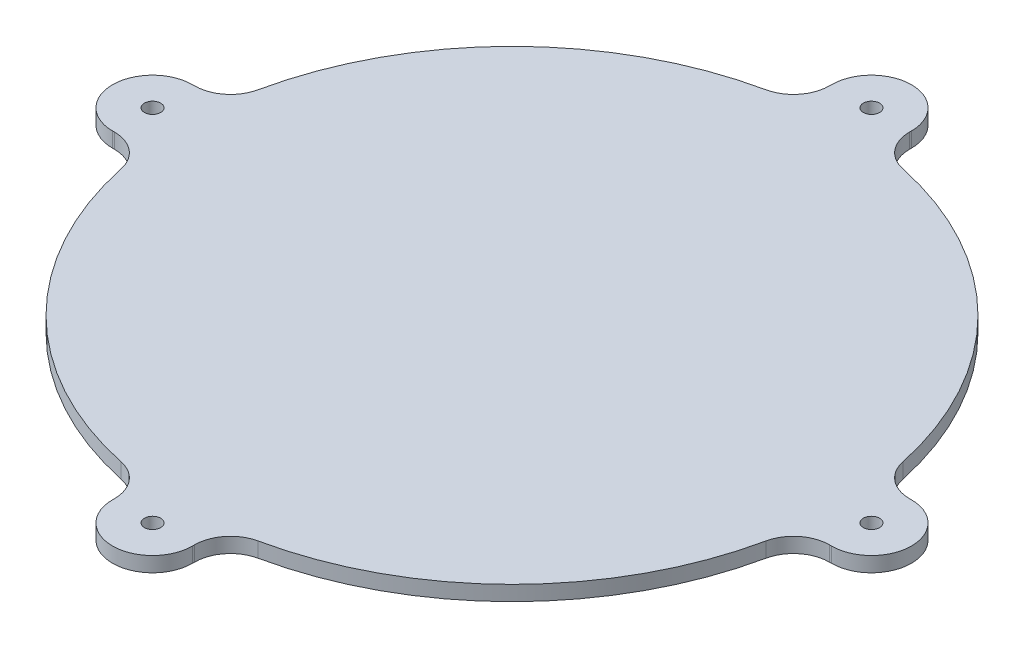
SolidWorks part; units mm, degrees
ref_plane "Front Plane" through (0, 0, 0) normal (0, 0, 1) x (1, 0, 0)
ref_plane "Top Plane" through (0, 0, 0) normal (0, 1, 0) x (1, 0, 0)
ref_plane "Right Plane" through (0, 0, 0) normal (1, 0, 0) x (0, 0, -1)
sketch "Sketch1" plane through (0, 0, 0) normal (0, 1, 0) x (1, 0, 0)
  line L1 (-8.4836, 76.2) -> (-8.4836, 69.3329)
  line L2 (8.4836, 76.2) -> (8.4836, 69.3329)
  line L3 (76.2, 8.4836) -> (69.3329, 8.4836)
  line L4 (76.2, -8.4836) -> (69.3329, -8.4836)
  line L5 (8.4836, -76.2) -> (8.4836, -69.3329)
  line L6 (-8.4836, -76.2) -> (-8.4836, -69.3329)
  line L7 (-76.2, -8.4836) -> (-69.3329, -8.4836)
  line L8 (-76.2, 8.4836) -> (-69.3329, 8.4836)
  circle A1 centre (0, 76.2) radius 1.7272
  circle A2 centre (76.2, 0) radius 1.7272
  circle A3 centre (0, -76.2) radius 1.7272
  circle A4 centre (-76.2, 0) radius 1.7272
  arc A5 (-8.4836, 76.2) -> (8.4836, 76.2) centre (0, 76.2) cw
  arc A6 (-8.4836, 69.3329) -> (-69.3329, 8.4836) centre (0, 0) ccw
  arc A7 (76.2, 8.4836) -> (76.2, -8.4836) centre (76.2, 0) cw
  arc A8 (8.4836, -76.2) -> (-8.4836, -76.2) centre (0, -76.2) cw
  arc A9 (-76.2, -8.4836) -> (-76.2, 8.4836) centre (-76.2, 0) cw
  arc A10 (69.3329, 8.4836) -> (8.4836, 69.3329) centre (0, 0) ccw
  arc A11 (8.4836, -69.3329) -> (69.3329, -8.4836) centre (0, 0) ccw
  arc A12 (-69.3329, -8.4836) -> (-8.4836, -69.3329) centre (0, 0) ccw
  point P17 (0, 0)
  point P36 (0, 0)
  dimension "D1" = 4
  dimension "D2" = 3.4544
  dimension "D4" = 4
  dimension "D5" = 152.4
  dimension "D6" = 76.2
  dimension "D8" = 8.4836
  dimension "D9" = 139.7
extrude "Boss-Extrude1" add sketch "Sketch1" along normal blind 3.175
fillet "Fillet2" radius 7.62 8 edges at (-8.4836, 1.5875, -69.3329) (8.4836, 1.5875, -69.3329) (69.3329, 1.5875, -8.4836) (69.3329, 1.5875, 8.4836) (8.4836, 1.5875, 69.3329) (-8.4836, 1.5875, 69.3329) (-69.3329, 1.5875, -8.4836) (-69.3329, 1.5875, 8.4836)
